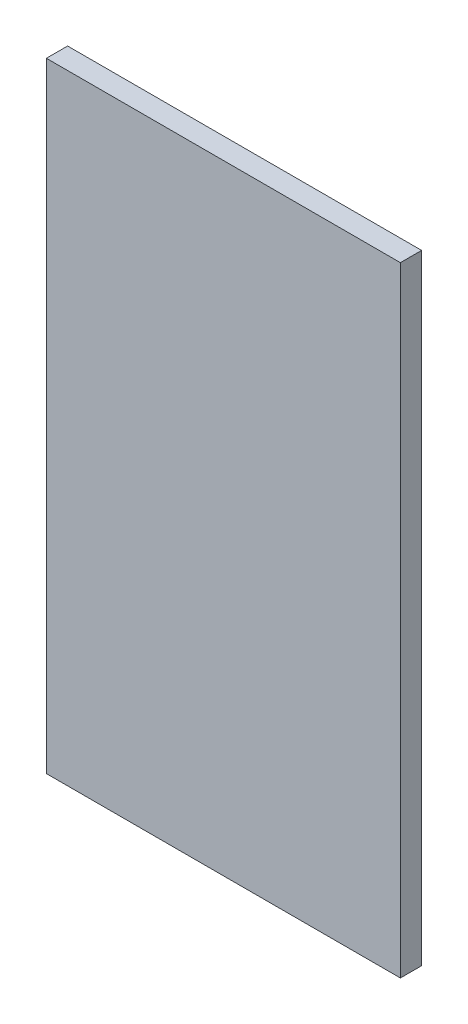
SolidWorks part; units mm, degrees
material "A-Glass Fiber"
ref_plane "Front" through (0, 0, 0) normal (0, 0, 1) x (1, 0, 0)
ref_plane "Top" through (0, 0, 0) normal (0, 1, 0) x (1, 0, 0)
ref_plane "Right" through (0, 0, 0) normal (1, 0, 0) x (0, 0, -1)
sketch "Sketch1" plane through (0, 0, 0) normal (0, 0, 1) x (1, 0, 0)
  line L1 (-50, -87.5) -> (50, -87.5)
  line L2 (-50, -87.5) -> (-50, 87.5)
  line L3 (-50, 87.5) -> (50, 87.5)
  line L4 (50, -87.5) -> (50, 87.5)
  line L5 (-50, -87.5) -> (50, 87.5) construction
  line L6 (-50, 87.5) -> (50, -87.5) construction
  point P0 (0, 0)
  dimension "D1" = 175
  dimension "D2" = 100
extrude "Boss-Extrude1" add sketch "Sketch1" along normal blind 6
